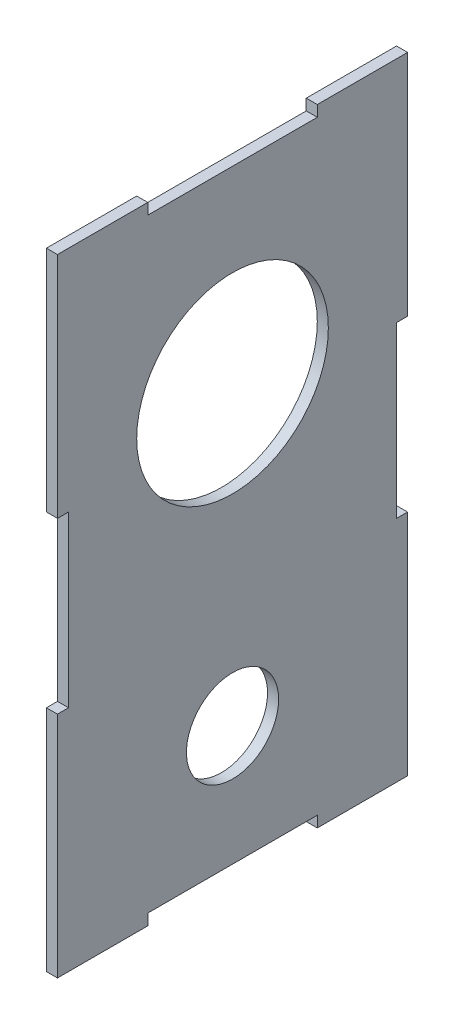
SolidWorks part; units mm, degrees
ref_plane "Alzado" through (0, 0, 0) normal (0, 0, 1) x (1, 0, 0)
ref_plane "Planta" through (0, 0, 0) normal (0, 1, 0) x (1, 0, 0)
ref_plane "Vista lateral" through (0, 0, 0) normal (1, 0, 0) x (0, 0, -1)
sketch "Croquis1" plane through (0, 0, 0) normal (1, 0, 0) x (0, 0, -1)
  line L0 (-23, 82) -> (23, 82)
  line L1 (-47.5, 85) -> (-23, 85)
  line L2 (-47.5, 85) -> (-47.5, 23)
  line L3 (-47.5, -85) -> (-23, -85)
  line L4 (47.5, 85) -> (47.5, 23)
  line L5 (23, 82) -> (23, 85)
  line L6 (-23, 82) -> (-23, 85)
  line L7 (-23, -82) -> (23, -82)
  line L8 (44.5, -23) -> (44.5, 23)
  line L9 (-44.5, -23) -> (-44.5, 23)
  line L10 (-44.5, -23) -> (-47.5, -23)
  line L11 (-44.5, 23) -> (-47.5, 23)
  line L12 (44.5, 23) -> (47.5, 23)
  line L13 (44.5, -23) -> (47.5, -23)
  line L14 (23, -82) -> (23, -85)
  line L15 (-23, -82) -> (-23, -85)
  line L16 (-47.5, -23) -> (-47.5, -85)
  line L17 (23, 85) -> (47.5, 85)
  line L18 (47.5, -23) -> (47.5, -85)
  line L19 (23, -85) -> (47.5, -85)
  circle A0 centre (0, 31) radius 26
  circle A1 centre (0, -49.5) radius 12.5
  point P13 (0, 82)
  point P22 (-44.5, 0)
  point P23 (44.5, 0)
  point P25 (0, -82)
  dimension "D3" = 52
  dimension "D5" = 25
  dimension "D1" = 95
  dimension "D2" = 170
  dimension "D4" = 54
  dimension "D6" = 35.5
  dimension "D7" = 47.5
  dimension "D8" = 47.5
  dimension "D9" = 46
  dimension "D10" = 3
  dimension "D11" = 46
  dimension "D12" = 46
  dimension "D13" = 3
  dimension "D14" = 3
  dimension "D15" = 46
  dimension "D16" = 3
  dimension "D17" = 62
  dimension "D18" = 24.5
  dimension "D19" = 62
  dimension "D20" = 24.5
extrude "Saliente-Extruir1" add sketch "Croquis1" along normal blind 3
